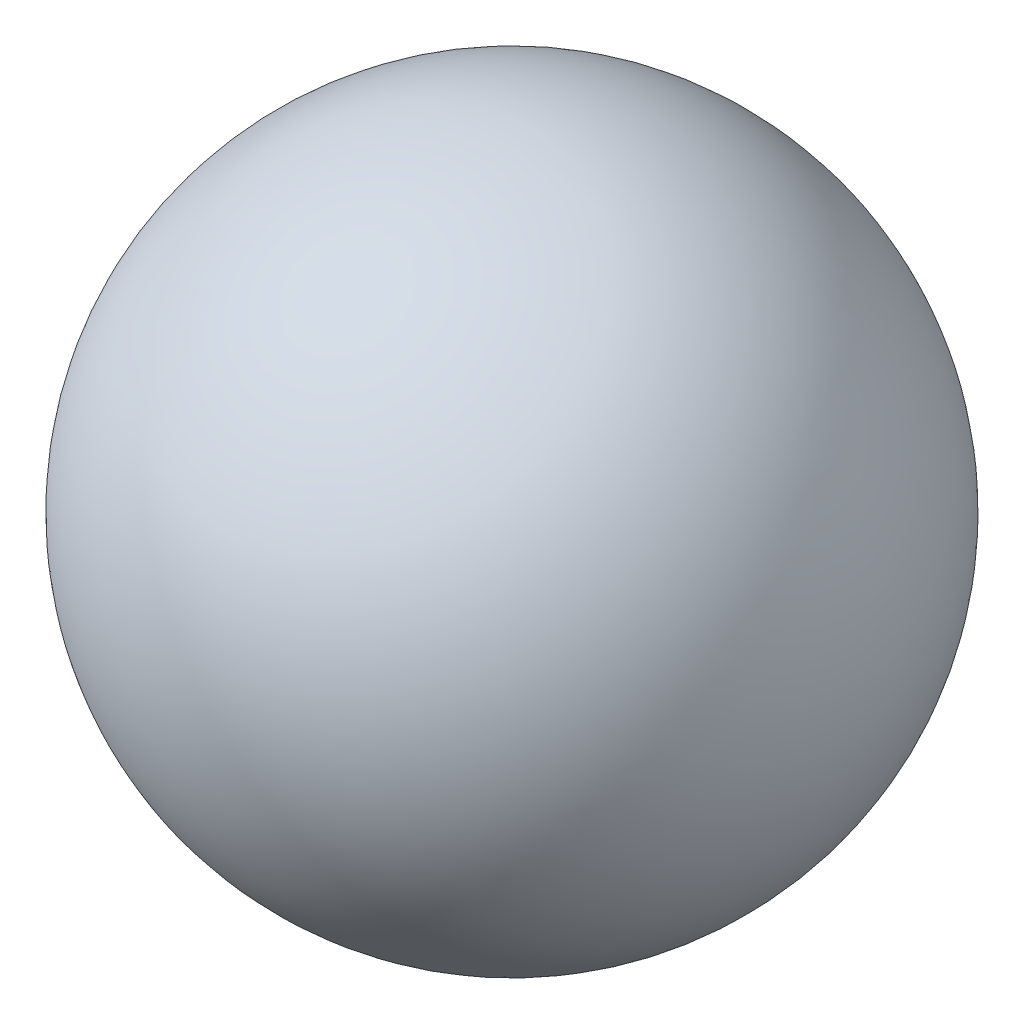
SolidWorks part; units mm, degrees
ref_plane "Front Plane" through (0, 0, 0) normal (1, 0, 0) x (0, 1, 0)
ref_plane "Top Plane" through (0, 0, 0) normal (0, 0, 1) x (0, 1, 0)
ref_plane "Right Plane" through (0, 0, 0) normal (0, 1, 0) x (-1, 0, 0)
sketch "Sketch1" plane through (0, 0, 0) normal (1, 0, 0) x (0, 1, 0)
  line L0 (0, 4) -> (0, -4)
  line L1 (0, 6.3971) -> (0, -5.9117) construction
  arc A0 (0, 4) -> (0, -4) centre (0, 0) ccw
  dimension "D1" = 4
revolve "Revolve1" add sketch "Sketch1" angle 360 about L1
